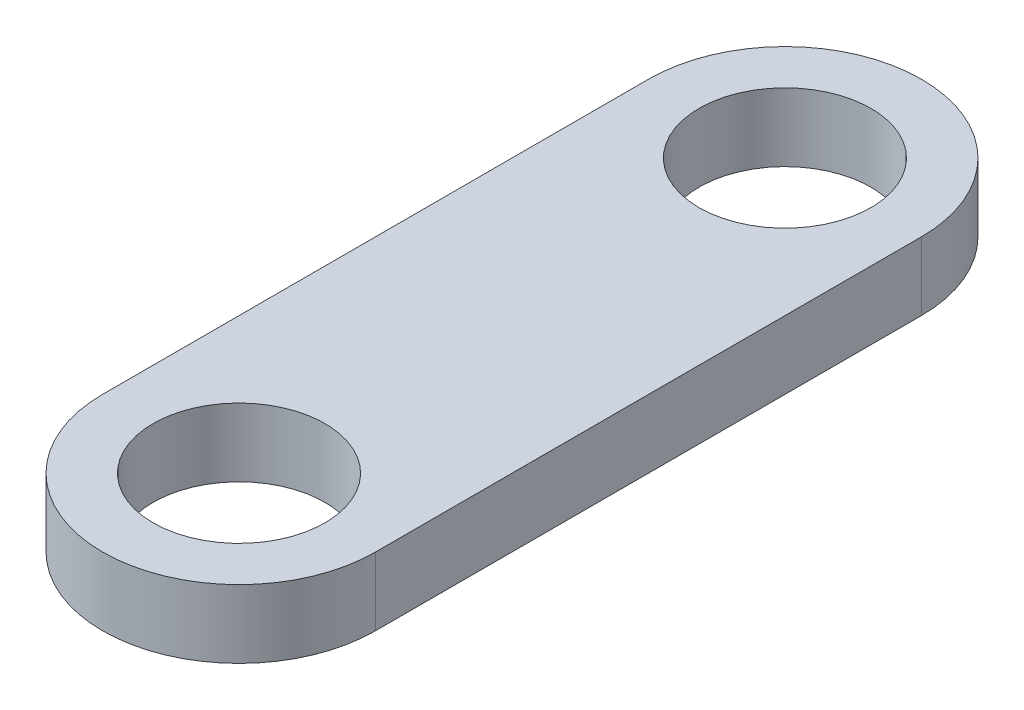
SolidWorks part; units mm, degrees
material "5052-H32"
ref_plane "X-Y Datum" through (0, 0, 0) normal (0, 0, 1) x (1, 0, 0)
ref_plane "X-Z Datum" through (0, 0, 0) normal (0, 1, 0) x (1, 0, 0)
ref_plane "Y-Z Datum" through (0, 0, 0) normal (1, 0, 0) x (0, 0, -1)
sketch "Sketch2" plane through (0, 0, 0) normal (0, 1, 0) x (1, 0, 0)
  line L7 (3.175, 0) -> (3.175, -12.7)
  line L8 (-3.175, 0) -> (-3.175, -12.7)
  circle A0 centre (0, 0) radius 2
  arc A2 (-3.175, 0) -> (3.175, 0) centre (0, 0) cw
  arc A3 (3.175, -12.7) -> (-3.175, -12.7) centre (0, -12.7) cw
  circle A4 centre (0, -12.7) radius 2
  dimension "D3" = 6.35
  dimension "D1" = 4
  dimension "D5" = 4
  dimension "D4" = 12.7
extrude "Boss-Extrude1" add sketch "Sketch2" along normal blind 1.5875
